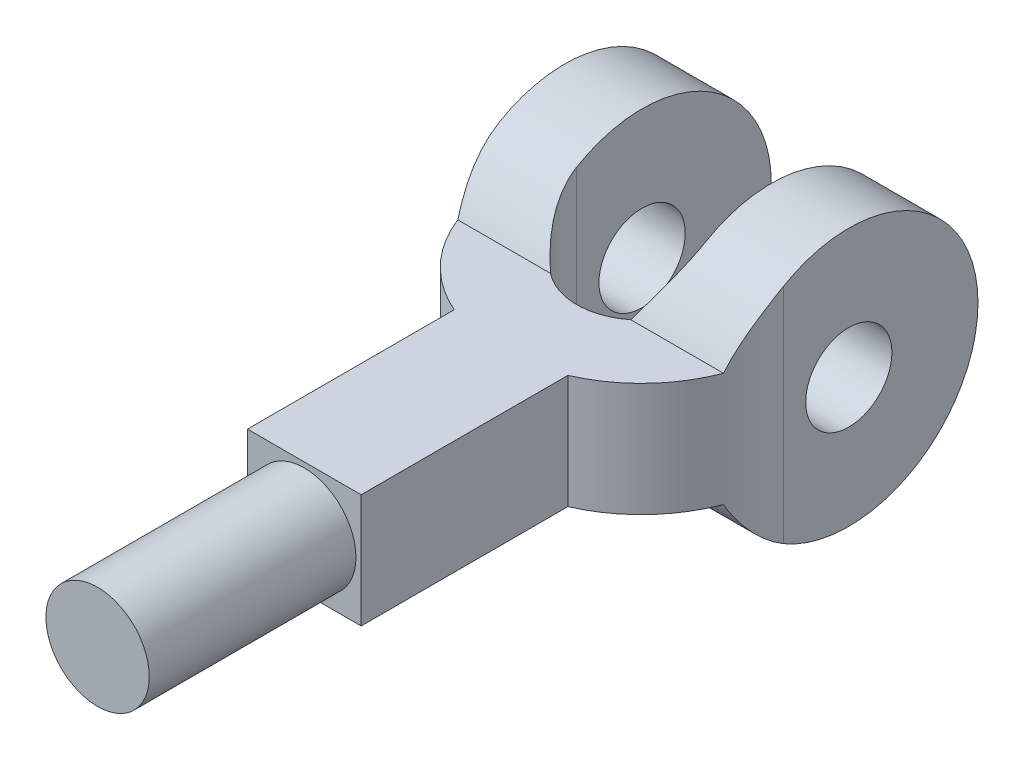
SolidWorks part; units mm, degrees
ref_plane "Front Plane" through (0, 0, 0) normal (0, 0, 1) x (1, 0, 0)
ref_plane "Top Plane" through (0, 0, 0) normal (0, 1, 0) x (1, 0, 0)
ref_plane "Right Plane" through (0, 0, 0) normal (1, 0, 0) x (0, 0, -1)
sketch "Sketch3" plane through (0, 0, 0) normal (0, 1, 0) x (1, 0, 0)
  line L2 (-12.5, 0) -> (-12.5, 50)
  line L3 (-12.5, 50) -> (-27.5, 50)
  line L4 (-27.5, 0) -> (-27.5, 50)
  line L6 (12.5, 0) -> (12.5, 37.66)
  line L7 (12.5, 37.66) -> (27.5, 37.66)
  line L8 (27.5, 0) -> (27.5, 37.66)
  line L9 (-11, -25.2042) -> (-11, -65.2042)
  line L10 (11, -25.2042) -> (11, -65.2042)
  line L11 (-11, -65.2042) -> (11, -65.2042)
  arc A0 (-12.5, 0) -> (12.5, 0) centre (0, 0) ccw
  arc A1 (-27.5, 0) -> (-11, -25.2042) centre (0, 0) ccw
  arc A2 (11, -25.2042) -> (27.5, 0) centre (0, 0) ccw
  dimension "D1" = 15
  dimension "D2" = 25
  dimension "D3" = 50
  dimension "D4" = 37.66
  dimension "D5" = 22
  dimension "D6" = 40
extrude "Boss-Extrude1" add sketch "Sketch3" along normal blind 50
sketch "Sketch4" plane through (27.5, 0, 0) normal (1, 0, 0) x (0, 0, -1)
  line L0 (37.66, 50) -> (37.66, 0) construction
  line L1 (0, 50) -> (37.66, 50) construction
  line L2 (0, 0) -> (37.66, 0) construction
  line L3 (12.66, 25) -> (-104.7982, 25) construction
  line L5 (-9.7899, 14) -> (-65.2042, 14)
  line L6 (-9.7899, 36) -> (-65.2042, 36)
  line L7 (-65.2042, 14) -> (-65.2042, 36)
  line L8 (-65.2042, 50) -> (-65.2042, 0) construction
  arc A0 (-9.7899, 14) -> (-9.7899, 36) centre (12.66, 25) ccw
  circle A1 centre (12.66, 25) radius 8.345
other "AlignGroup1" parameters "D1"=42.455, "D2"=35.3839, "D3"=0
extrude "Cut-Extrude1" cut sketch "Sketch4" against normal through all flip side to cut
sketch "Sketch5" plane through (0, 0, 65.2042) normal (0, 0, 1) x (1, 0, 0)
  line L0 (-11, 14) -> (11, 14) construction
  line L3 (11, 36) -> (11, 14) construction
  circle A0 centre (0, 25) radius 10
  dimension "D1" = 20
  dimension "D2" = 11
  dimension "D3" = 11
extrude "Boss-Extrude2" add sketch "Sketch5" along normal blind 40
